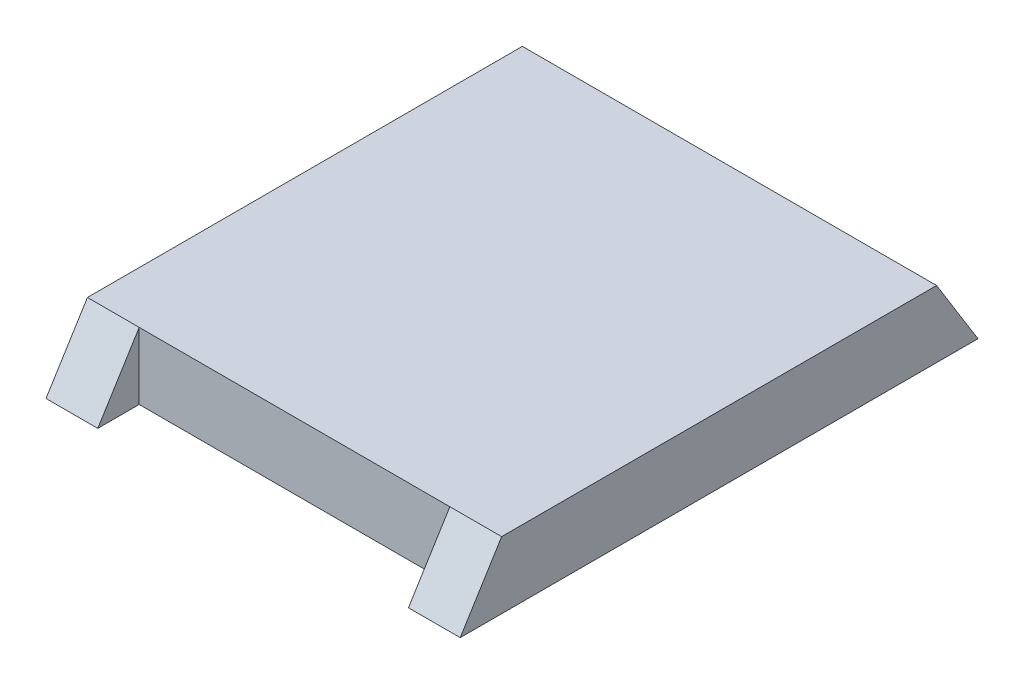
SolidWorks part; units mm, degrees
ref_plane "Front Plane" through (0, 0, 0) normal (0, 0, 1) x (1, 0, 0)
ref_plane "Top Plane" through (0, 0, 0) normal (0, 1, 0) x (1, 0, 0)
ref_plane "Right Plane" through (0, 0, 0) normal (1, 0, 0) x (0, 0, -1)
sketch "Sketch1" plane through (0, 0, 0) normal (0, 1, 0) x (1, 0, 0)
  line L1 (-400, -500) -> (400, -500)
  line L2 (-400, -500) -> (-400, 500)
  line L3 (-400, 500) -> (400, 500)
  line L4 (400, -500) -> (400, 500)
  line L5 (-400, -500) -> (400, 500) construction
  line L6 (-400, 500) -> (400, -500) construction
  point P0 (0, 0)
  dimension "D1" = 800
  dimension "D2" = 1000
extrude "Boss-Extrude1" add sketch "Sketch1" along normal blind 129 contours L2 L1 L4 L3
sketch "Sketch2" plane through (-400, 0, 0) normal (-1, 0, 0) x (0, 0, 1)
  line L0 (500, 0) -> (420, 0)
  line L1 (500, 0) -> (-500, 0) construction
  line L2 (420, 0) -> (420, 129)
  line L3 (500, 129) -> (-500, 129) construction
  line L4 (420, 129) -> (500, 129)
  line L5 (500, 129) -> (500, -5.7881)
  line L6 (500, 0) -> (420, 129)
  line M5 (500, 0) -> (500, 129)
  line M6 (500, 129) -> (-500, 129)
  dimension "D1" = 80
extrude "Cut-Extrude1" cut sketch "Sketch2" against normal blind 800 contours L6 M5 M6
sketch "Sketch3" plane through (0, 223.9486, 361.1171) normal (0, 0.527, 0.8498) x (1, 0, 0)
  line L0 (-400, -263.5174) -> (-300, -263.5174)
  line L1 (-400, -263.5174) -> (400, -263.5174) construction
  line L2 (-300, -263.5174) -> (-300, -111.7248)
  line L3 (400, -111.7248) -> (-400, -111.7248) construction
  line L4 (-300, -111.7248) -> (-400, -111.7248)
  line L5 (-400, -111.7248) -> (-400, -263.5174)
  line L7 (400, -111.7248) -> (300, -111.7248)
  line L8 (400, -111.7248) -> (400, -263.5174)
  line L9 (400, -263.5174) -> (300, -263.5174)
  line L10 (300, -111.7248) -> (300, -263.5174)
  point P15 (0, 0)
  point P16 (0, 0)
  dimension "D1" = 100
  dimension "D2" = 100
sketch "Sketch5" plane through (400, 0, 0) normal (1, 0, 0) x (0, 0, -1)
  line L0 (-420, 129) -> (-420, 0)
  line L1 (-500, 0) -> (500, 0) construction
sketch "Sketch6" plane through (-400, 0, 0) normal (-1, 0, 0) x (0, 0, 1)
  line L0 (420, 129) -> (420, 0)
  line L1 (500, 0) -> (-500, 0) construction
sketch "Sketch8" plane through (0, 0, 0) normal (0, -1, 0) x (1, 0, 0)
  line L0 (410.7236, 420) -> (-400, 420)
  line L1 (300, 500) -> (300, 420)
  line L2 (-300, 500) -> (-300, 420)
  point P9 (0, 0)
sketch "Sketch17" plane through (0, 223.9486, 361.1171) normal (0, 0.527, 0.8498) x (1, 0, 0)
  line L1 (-300, -111.7248) -> (300, -111.7248)
  line L2 (-300, -111.7248) -> (-300, -263.5174)
  line L3 (-300, -263.5174) -> (300, -263.5174)
  line L4 (300, -111.7248) -> (300, -263.5174)
extrude "Cut-Extrude2" cut sketch "Sketch17" against normal blind 275
sketch "Sketch25" plane through (0, 0, -500) normal (0, 0, -1) x (-1, 0, 0)
  line L0 (-400, 0) -> (-300, 0)
  line L1 (400, 0) -> (-400, 0) construction
  line L2 (-300, 0) -> (-300, 129)
  line L3 (400, 129) -> (-400, 129) construction
  line L4 (-300, 129) -> (-400, 129)
  line L5 (-400, 129) -> (-400, 0)
  line L7 (400, 129) -> (300, 129)
  line L8 (400, 129) -> (400, 0)
  line L9 (400, 0) -> (300, 0)
  line L10 (300, 129) -> (300, 0)
  line L11 (-300, 129) -> (300, 129)
  line L13 (-300, 0) -> (300, 0)
  line M3 (-400, 0) -> (400, 0)
  line M5 (400, 129) -> (-400, 129)
  dimension "D1" = 100
  dimension "D2" = 100
extrude "Cut-Extrude4" cut sketch "Sketch25" against normal blind 80 contours L10 L2 M5 M3
sketch "Sketch27" plane through (-400, 0, 0) normal (-1, 0, 0) x (0, 0, 1)
  line L0 (-500, 0) -> (-420, 0)
  line L1 (500, 0) -> (-500, 0) construction
  line L2 (-500, 0) -> (-500, 129)
  line L3 (-500, 129) -> (-420, 129)
  line L4 (420, 129) -> (-500, 129) construction
  line L5 (-500, 0) -> (-420, 129)
  dimension "D1" = 80
sketch "Sketch28" plane through (-300, 0, 0) normal (1, 0, 0) x (0, 0, -1)
  line L0 (420, 129) -> (500, 129)
  line L1 (500, 129) -> (500, 0)
  line L2 (500, 0) -> (420, 129)
extrude "Cut-Extrude5" cut sketch "Sketch28" against normal blind 100
sketch "Sketch29" plane through (300, 0, 0) normal (-1, 0, 0) x (0, 0, 1)
  line L0 (-420, 129) -> (-500, 129)
  line L1 (-500, 129) -> (-500, 0)
  line L2 (-500, 0) -> (-420, 129)
extrude "Cut-Extrude6" cut sketch "Sketch29" against normal blind 100
sketch "Sketch31" plane through (300, 0, 0) normal (-1, 0, 0) x (0, 0, 1)
  line L0 (420, 129) -> (420, 0)
  line L1 (420, 0) -> (211.9875, 0)
  line L2 (211.9875, 0) -> (420, 129)
extrude "Boss-Extrude4" add sketch "Sketch31" along normal blind 600
